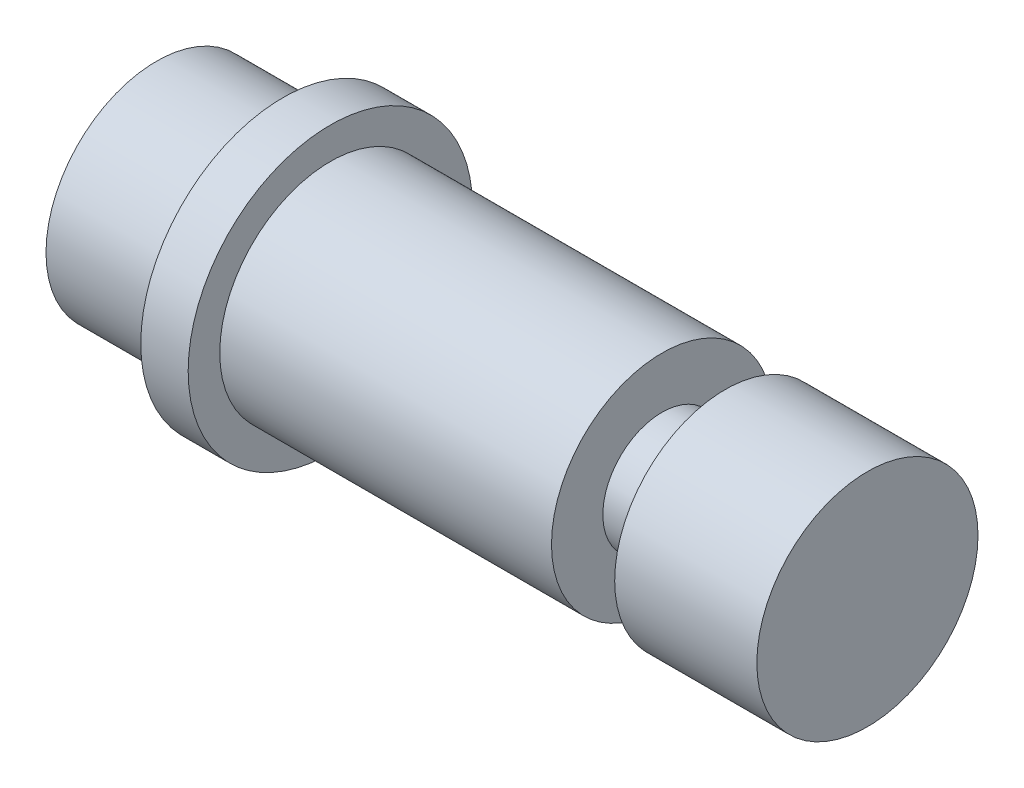
SolidWorks part; units mm, degrees
ref_plane "Alzado" through (0, 0, 0) normal (0, 0, 1) x (1, 0, 0)
ref_plane "Planta" through (0, 0, 0) normal (0, 1, 0) x (1, 0, 0)
ref_plane "Vista lateral" through (0, 0, 0) normal (1, 0, 0) x (0, 0, -1)
sketch "Croquis1" plane through (0, 0, 0) normal (0, 0, 1) x (1, 0, 0)
  line L0 (0, 0) -> (45, 0)
  line L1 (45, 0) -> (45, 7)
  line L2 (45, 7) -> (36, 7)
  line L3 (36, 7) -> (36, 3.75)
  line L4 (36, 3.75) -> (32, 3.75)
  line L5 (32, 3.75) -> (32, 7)
  line L6 (32, 7) -> (11, 7)
  line L7 (11, 7) -> (11, 9)
  line L8 (11, 9) -> (8, 9)
  line L9 (8, 9) -> (8, 7)
  line L10 (8, 7) -> (0, 7)
  line L11 (0, 7) -> (0, 0)
  line L12 (0, 0) -> (0.023, 0.0493)
  line L13 (0, 0) -> (-1.117, 0) construction
  dimension "D1" = 45
  dimension "D2" = 9
  dimension "D3" = 25
  dimension "D4" = 3
  dimension "D5" = 4
  dimension "D6" = 9
  dimension "D7" = 7
  dimension "D8" = 3.75
revolve "Revolución1" add sketch "Croquis1" angle 360 about L13
